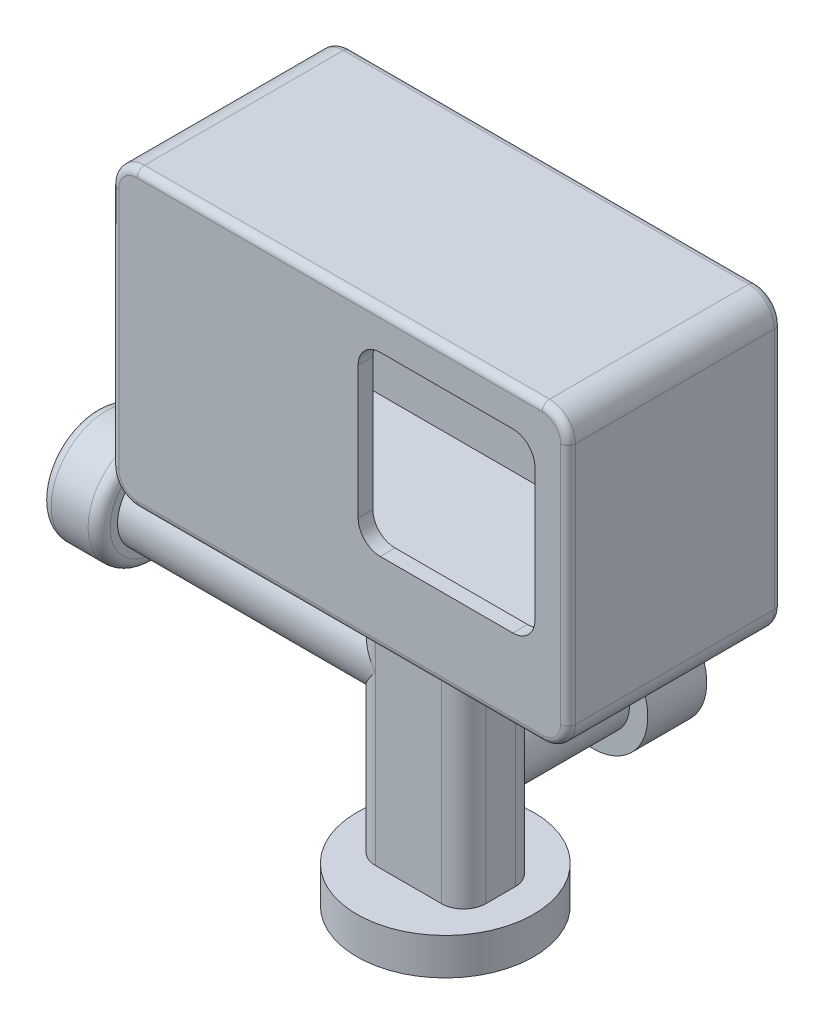
SolidWorks part; units mm, degrees
ref_plane "Front Plane" through (0, 0, 0) normal (0, 0, 1) x (1, 0, 0)
ref_plane "Top Plane" through (0, 0, 0) normal (0, 1, 0) x (1, 0, 0)
ref_plane "Right Plane" through (0, 0, 0) normal (1, 0, 0) x (0, 0, -1)
sketch "Sketch1" plane through (0, 0, 0) normal (0, 0, 1) x (1, 0, 0)
  line L4 (29.5, 80) -> (29.5, 47)
  line L5 (27.5, 45) -> (-27.5, 45)
  line L6 (-29.5, 47) -> (-29.5, 80)
  line L7 (-27.5, 82) -> (27.5, 82)
  line L8 (31, 80) -> (31, 47)
  line L9 (27.5, 43.5) -> (-27.5, 43.5)
  line L10 (-31, 47) -> (-31, 80)
  line L11 (-27.5, 83.5) -> (27.5, 83.5)
  arc A4 (29.5, 80) -> (27.5, 82) centre (27.5, 80) ccw
  arc A5 (27.5, 45) -> (29.5, 47) centre (27.5, 47) ccw
  arc A6 (-29.5, 47) -> (-27.5, 45) centre (-27.5, 47) ccw
  arc A7 (-27.5, 82) -> (-29.5, 80) centre (-27.5, 80) ccw
  arc A8 (27.5, 43.5) -> (31, 47) centre (27.5, 47) ccw
  arc A9 (-31, 47) -> (-27.5, 43.5) centre (-27.5, 47) ccw
  arc A10 (-27.5, 83.5) -> (-31, 80) centre (-27.5, 80) ccw
  arc A11 (31, 80) -> (27.5, 83.5) centre (27.5, 80) ccw
  dimension "D1" = 1.5
extrude "Boss-Extrude1" add sketch "Sketch1" against normal blind 27
sketch "Sketch2" plane through (0, 0, 0) normal (0, 0, 1) x (1, 0, 0)
  line L4 (27.5, 83.5) -> (-27.5, 83.5)
  line L5 (-31, 80) -> (-31, 47)
  line L6 (-27.5, 43.5) -> (27.5, 43.5)
  line L7 (31, 47) -> (31, 80)
  line L8 (27.5, 83.5) -> (-27.5, 83.5)
  line L9 (-31, 80) -> (-31, 47)
  line L10 (-27.5, 43.5) -> (27.5, 43.5)
  line L11 (31, 47) -> (31, 80)
  line L33 (23.5, 78.5) -> (5.5, 78.5)
  line L34 (2.5, 75.5) -> (2.5, 57.5)
  line L35 (5.5, 54.5) -> (23.5, 54.5)
  line L36 (26.5, 57.5) -> (26.5, 75.5)
  line L37 (23.5, 78.5) -> (5.5, 78.5)
  line L38 (2.5, 75.5) -> (2.5, 57.5)
  line L39 (5.5, 54.5) -> (23.5, 54.5)
  line L40 (26.5, 57.5) -> (26.5, 75.5)
  arc A4 (31, 80) -> (27.5, 83.5) centre (27.5, 80) ccw
  arc A5 (-27.5, 83.5) -> (-31, 80) centre (-27.5, 80) ccw
  arc A6 (-31, 47) -> (-27.5, 43.5) centre (-27.5, 47) ccw
  arc A7 (27.5, 43.5) -> (31, 47) centre (27.5, 47) ccw
  arc A8 (31, 80) -> (27.5, 83.5) centre (27.5, 80) ccw
  arc A9 (-27.5, 83.5) -> (-31, 80) centre (-27.5, 80) ccw
  arc A10 (-31, 47) -> (-27.5, 43.5) centre (-27.5, 47) ccw
  arc A11 (27.5, 43.5) -> (31, 47) centre (27.5, 47) ccw
  arc A36 (26.5, 75.5) -> (23.5, 78.5) centre (23.5, 75.5) ccw
  arc A37 (5.5, 78.5) -> (2.5, 75.5) centre (5.5, 75.5) ccw
  arc A38 (2.5, 57.5) -> (5.5, 54.5) centre (5.5, 57.5) ccw
  arc A39 (23.5, 54.5) -> (26.5, 57.5) centre (23.5, 57.5) ccw
  arc A40 (26.5, 75.5) -> (23.5, 78.5) centre (23.5, 75.5) ccw
  arc A41 (5.5, 78.5) -> (2.5, 75.5) centre (5.5, 75.5) ccw
  arc A42 (2.5, 57.5) -> (5.5, 54.5) centre (5.5, 57.5) ccw
  arc A43 (23.5, 54.5) -> (26.5, 57.5) centre (23.5, 57.5) ccw
  dimension "D1" = 0
  dimension "D2" = 0
extrude "Boss-Extrude2" add sketch "Sketch2" along normal blind 2
sketch "Sketch3" plane through (0, 43.5, 0) normal (0, -1, 0) x (1, 0, 0)
  line L0 (0, -27) -> (0, 2) construction
  line L1 (0.405, -16.7128) -> (-5, -153.9931) construction
  line L2 (-5.6504, 219.5) -> (0.4026, -13.4973) construction
  line L4 (-7.5, -7.3323) -> (7.5, -7.3323)
  line L5 (-7.5, -7.3323) -> (-7.5, -17.3323)
  line L6 (-7.5, -17.3323) -> (7.5, -17.3323)
  line L7 (7.5, -7.3323) -> (7.5, -17.3323)
  line L8 (-31, -12.3323) -> (31.0779, -12.3323) construction
  line L9 (-27.5, -27) -> (27.5, -27) construction
  line L10 (-27.5, 2) -> (27.5, 2) construction
  dimension "D1" = 7.5
  dimension "D2" = 15
  dimension "D3" = 10
  dimension "D4" = 5
extrude "Boss-Extrude3" add sketch "Sketch3" along normal blind 40
sketch "Sketch4" plane through (0, 3.5, 0) normal (0, -1, 0) x (1, 0, 0)
  line L0 (-7.5, -12.3323) -> (0, -12.3323) construction
  line L1 (-7.5, -7.3323) -> (-7.5, -17.3323) construction
  line L2 (0, -12.3323) -> (0, -7.3323) construction
  line L3 (7.5, -7.3323) -> (-7.5, -7.3323) construction
  circle A0 centre (0, -12.3323) radius 12
extrude "Boss-Extrude4" add sketch "Sketch4" against normal blind 5
fillet "Fillet2" radius 3 4 edges at (7.5, 26, -7.3323) (-7.5, 26, -7.3323) (-7.5, 26, -17.3323) (7.5, 26, -17.3323)
sketch "Sketch5" plane through (-7.5, 0, 0) normal (-1, 0, 0) x (0, 0, 1)
  line L0 (-12.3323, 43.5) -> (-12.3323, 8.5) construction
  line L3 (-12.3323, 3.5) -> (-12.3323, 8.5) construction
  line L4 (-0.3323, 8.5) -> (-24.3323, 8.5) construction
  circle A1 centre (-12.3323, 31.2278) radius 5
extrude "Boss-Extrude5" add sketch "Sketch5" along normal blind 32 and the other way blind 10
sketch "Sketch6" plane through (-39.5, 0, 0) normal (-1, 0, 0) x (0, 0, 1)
  circle A1 centre (-12.3323, 31.2278) radius 7.5
extrude "Boss-Extrude6" add sketch "Sketch6" along normal blind 8
sketch "Sketch7" plane through (-31, 0, 0) normal (-1, 0, 0) x (0, 0, 1)
  line L0 (-12.5, 83.5) -> (-12.5, 43.5) construction
  line L1 (-27, 83.5) -> (2, 83.5) construction
  line L2 (-27, 43.5) -> (2, 43.5) construction
  circle A0 centre (-12.5, 71.5) radius 5
  circle A1 centre (-12.5, 56.5) radius 5
  dimension "D1" = 12
  dimension "D2" = 15
extrude "Boss-Extrude7" add sketch "Sketch7" along normal blind 5
sketch "Sketch8" plane through (0, 0, -27) normal (0, 0, -1) x (-1, 0, 0)
  line L8 (-29, 80) -> (-29, 47)
  line L9 (-27.5, 45.5) -> (27.5, 45.5)
  line L10 (29, 47) -> (29, 80)
  line L11 (27.5, 81.5) -> (-27.5, 81.5)
  line L12 (-29, 80) -> (-29, 47)
  line L13 (-27.5, 45.5) -> (27.5, 45.5)
  line L14 (29, 47) -> (29, 80)
  line L15 (27.5, 81.5) -> (-27.5, 81.5)
  arc A8 (-27.5, 81.5) -> (-29, 80) centre (-27.5, 80) ccw
  arc A9 (-29, 47) -> (-27.5, 45.5) centre (-27.5, 47) ccw
  arc A10 (27.5, 45.5) -> (29, 47) centre (27.5, 47) ccw
  arc A11 (29, 80) -> (27.5, 81.5) centre (27.5, 80) ccw
  arc A12 (-27.5, 81.5) -> (-29, 80) centre (-27.5, 80) ccw
  arc A13 (-29, 47) -> (-27.5, 45.5) centre (-27.5, 47) ccw
  arc A14 (27.5, 45.5) -> (29, 47) centre (27.5, 47) ccw
  arc A15 (29, 80) -> (27.5, 81.5) centre (27.5, 80) ccw
  dimension "D1" = 2
extrude "Boss-Extrude8" add sketch "Sketch8" against normal blind 1 separate body
fillet "Fillet3" radius 1 16 edges at (29.9749, 82.4749, 2) (31, 63.5, 2) (29.9749, 44.5251, 2) (0, 43.5, 2) (-29.9749, 44.5251, 2) (-31, 63.5, 2) (-29.9749, 82.4749, 2) (0, 83.5, 2) (31, 63.5, -27) (29.9749, 44.5251, -27) (0, 43.5, -27) (-29.9749, 44.5251, -27) (-31, 63.5, -27) (-29.9749, 82.4749, -27) (0, 83.5, -27) (29.9749, 82.4749, -27)
fillet "Fillet4" radius 1.5 2 edges at (-39.5, 31.2278, -4.8323) (-47.5, 31.2278, -4.8323)
fillet "Fillet5" radius 1 2 edges at (-36, 56.5, -7.5) (-36, 71.5, -7.5)
sketch "Sketch9" plane through (0, 0, -17.3323) normal (0, 0, -1) x (-1, 0, 0)
  line L0 (27.5, 43.5) -> (-27.5, 43.5) construction
  circle A0 centre (0, 19.5) radius 5
  dimension "D1" = 24
extrude "Boss-Extrude9" add sketch "Sketch9" along normal blind 15 and the other way blind 5
sketch "Sketch11" plane through (0, 0, -32.3323) normal (0, 0, -1) x (-1, 0, 0)
  circle A0 centre (0, 19.5) radius 7.5
extrude "Boss-Extrude10" add sketch "Sketch11" along normal blind 8
